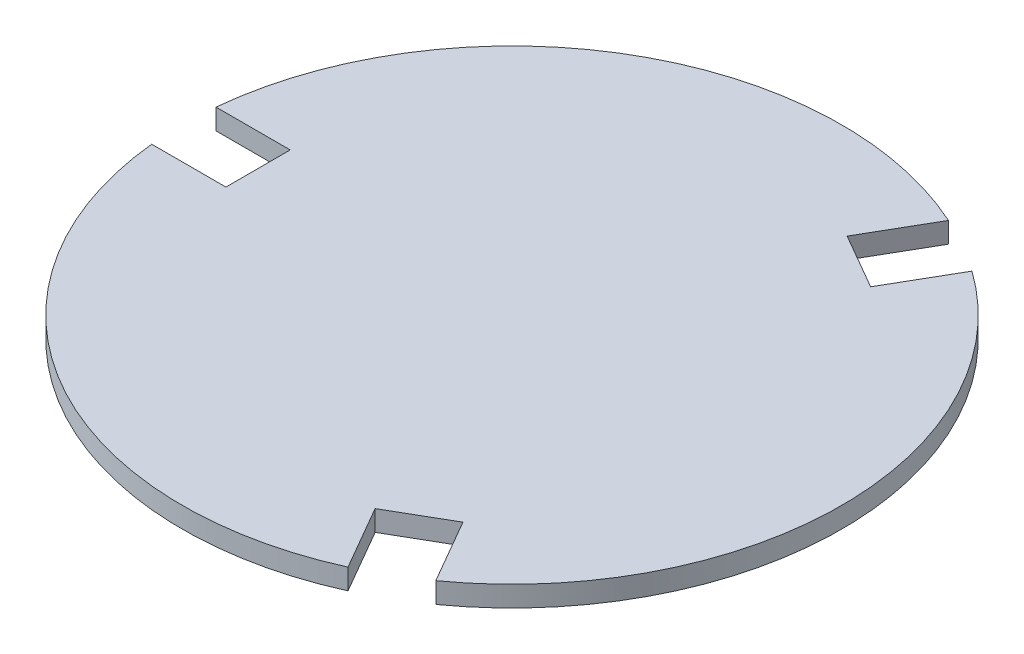
SolidWorks part; units mm, degrees
ref_plane "Front Plane" through (0, 0, 0) normal (0, 0, 1) x (1, 0, 0)
ref_plane "Top Plane" through (0, 0, 0) normal (0, 1, 0) x (1, 0, 0)
ref_plane "Right Plane" through (0, 0, 0) normal (1, 0, 0) x (0, 0, -1)
sketch "Sketch1" plane through (0, 0, 0) normal (0, 1, 0) x (1, 0, 0)
  circle A0 centre (0, 0) radius 50.8
  dimension "D1" = 101.6
extrude "Extrude1" add sketch "Sketch1" along normal blind 3.175
sketch "Sketch3" plane through (0, 3.175, 0) normal (0, 1, 0) x (-1, 0, 0)
  line L0 (50.8, 0) -> (0, 0) construction
  line L1 (42.1779, -4.953) -> (39.128, -4.953)
  line L2 (50.558, -4.953) -> (42.1779, -4.953)
  line L3 (39.128, -4.953) -> (39.128, 4.953)
  line L4 (50.558, 4.953) -> (42.303, 4.953)
  line L5 (50.558, -4.953) -> (50.558, 4.953) construction
  line L6 (39.128, -8.1544) -> (39.128, 10.5364) construction
  line L7 (50.2723, -7.303) -> (33.1572, -7.303) construction
  line L8 (34.048, -9.4532) -> (34.048, -2.9029) construction
  line L9 (50.558, -4.953) -> (52.8754, -4.953)
  line L10 (52.8754, -4.953) -> (52.8754, 4.953)
  line L11 (52.8754, 4.953) -> (50.558, 4.953)
  line L12 (39.128, 4.953) -> (42.303, 4.953)
  line L13 (0, 0) -> (20.581, -35.6473) construction
  circle A0 centre (0, 0) radius 50.8 construction
  point P9 (35.2477, 0)
  dimension "D1" = 4.953
  dimension "D2" = 11.43
  dimension "D3" = 2.35
  dimension "D4" = 5.08
  dimension "D5" = 13.7474
  dimension "D6" = 60
  dimension "D7" = 41.162
extrude "Extrude2" cut sketch "Sketch3" against normal through all
sketch "Sketch5" plane through (0, 0, 0) normal (1, 0, 0) x (0, 0, -1)
  line L0 (0, 38.1783) -> (0, -21.3827) construction
pattern_circular "CirPattern1" count 2 over 120 about axis through (0, 38.1783, 0) along (0, -1, 0) of "Extrude2"
pattern_circular "CirPattern2" count 2 over 120 about axis through (0, 0, 0) along (0, 1, 0) of "Extrude2"
